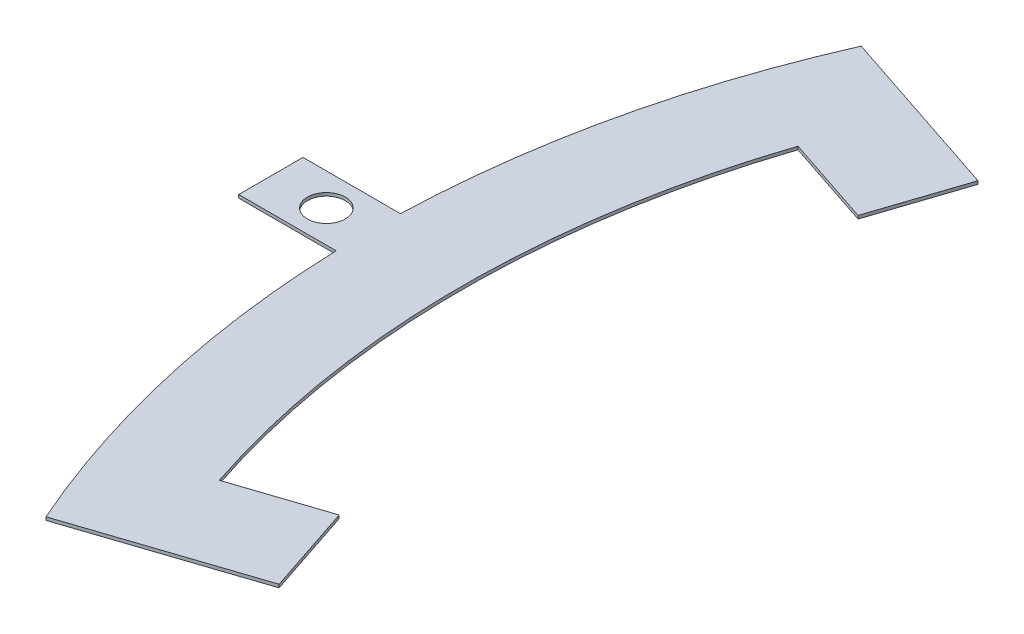
SolidWorks part; units mm, degrees
material "Galvanized Steel"
ref_plane "Front Plane" through (0, 0, 0) normal (0, 0, 1) x (1, 0, 0)
ref_plane "Top Plane" through (0, 0, 0) normal (0, 1, 0) x (1, 0, 0)
ref_plane "Right Plane" through (0, 0, 0) normal (1, 0, 0) x (0, 0, -1)
sketch "Sketch1" plane through (0, 0, 0) normal (0, 1, 0) x (1, 0, 0)
  line L0 (-1000, 0) -> (49000, 0) construction
  line L1 (0, -1000) -> (0, 49000) construction
  line L2 (-500, 866.0254) -> (24500, -42435.2448) construction
  line L3 (-500, -866.0254) -> (24500, 42435.2448) construction
  line L4 (-246.8222, 82.0488) -> (-275.2905, 91.5123)
  line L5 (-237.3587, 110.5171) -> (-292.6929, 128.9113)
  line L8 (-319.6623, 10.1634) -> (-350.4847, 10.1634)
  line L9 (-319.6623, -10.1634) -> (-350.4847, -10.1634)
  line L10 (-350.4847, 10.1634) -> (-350.4847, -10.1634)
  line L11 (-237.3587, -110.5171) -> (-292.6929, -128.9113)
  line L12 (-246.8222, -82.0488) -> (-275.2905, -91.5123)
  line L13 (-237.3587, -110.5171) -> (-246.8222, -82.0488)
  line L14 (-246.8222, 82.0488) -> (-237.3587, 110.5171)
  circle A0 centre (0, 0) radius 250 construction
  arc A2 (-292.6929, 128.9113) -> (-319.6623, 10.1634) centre (0, 0) ccw
  arc A3 (-275.2905, 91.5123) -> (-275.2905, -91.5123) centre (0, 0) ccw
  arc A7 (-319.6623, -10.1634) -> (-292.6929, -128.9113) centre (0, 0) ccw
  circle A9 centre (-332.928, 0) radius 6
  dimension "D1" = 500
  dimension "D8" = 319.8238
  dimension "D9" = 290.1023
  dimension "D15" = 12
  dimension "D10" = 290.1023
  dimension "D2" = 60
  dimension "D3" = 60
  dimension "D6" = 30
  dimension "D7" = 30
  dimension "D4" = 30
  dimension "D5" = 30
  dimension "D13" = 20.3268
  dimension "D16" = 332.928
  dimension "D17" = 20.3268
  dimension "D18" = 90
  dimension "D19" = 350.4847
extrude "Boss-Extrude1" add sketch "Sketch1" along normal blind 1
